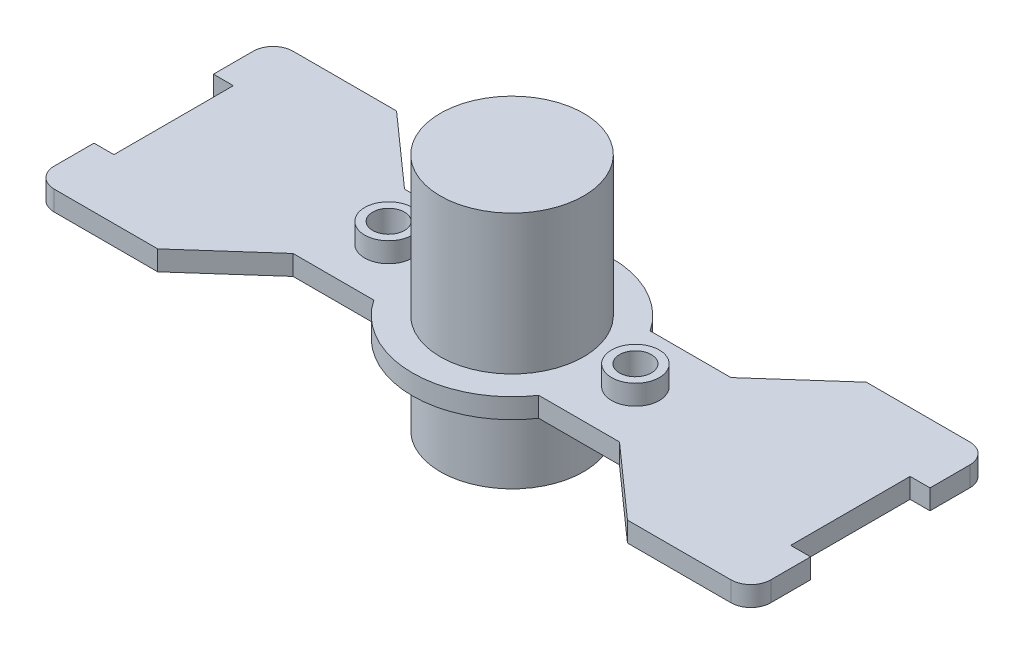
SolidWorks part; units mm, degrees
ref_plane "前视基准面" through (0, 0, 0) normal (0, 0, 1) x (1, 0, 0)
ref_plane "上视基准面" through (0, 0, 0) normal (0, 1, 0) x (1, 0, 0)
ref_plane "右视基准面" through (0, 0, 0) normal (1, 0, 0) x (0, 0, -1)
sketch "草图1" plane through (0, 0, 0) normal (0, 1, 0) x (1, 0, 0)
  line L0 (0, 0) -> (0, 25) construction
  line L1 (-20.7123, 14) -> (-41, 14)
  line L2 (-41, 14) -> (-59, 30)
  line L3 (-59, 30) -> (-90, 30)
  line L4 (-90, 30) -> (-90, 15)
  line L5 (-90, 15) -> (-85, 15)
  line L6 (-85, 15) -> (-85, -15)
  line L7 (-85, -15) -> (-90, -15)
  line L8 (-90, -15) -> (-90, -30)
  line L9 (-90, -30) -> (-59, -30)
  line L10 (-59, -30) -> (-41, -14)
  line L11 (-41, -14) -> (-20.7123, -14)
  line L12 (0, 0) -> (-85, 0) construction
  line L13 (90, -30) -> (59, -30)
  line L14 (59, 30) -> (90, 30)
  line L15 (41, -14) -> (20.7123, -14)
  line L16 (59, -30) -> (41, -14)
  line L17 (90, -15) -> (90, -30)
  line L18 (85, -15) -> (90, -15)
  line L19 (85, 15) -> (85, -15)
  line L20 (90, 15) -> (85, 15)
  line L21 (90, 30) -> (90, 15)
  line L22 (41, 14) -> (59, 30)
  line L23 (20.7123, 14) -> (41, 14)
  arc A0 (-20.7123, -14) -> (20.7123, -14) centre (0, 0) ccw
  arc A1 (20.7123, 14) -> (-20.7123, 14) centre (0, 0) ccw
  point P17 (0, 0)
  point P18 (0, 0)
  point P19 (0, 0)
  dimension "D1" = 50
  dimension "D2" = 41
  dimension "D3" = 118
  dimension "D4" = 180
  dimension "D5" = 170
  dimension "D6" = 30
  dimension "D7" = 60
  dimension "D8" = 28
extrude "凸台-拉伸1" add sketch "草图1" along normal blind 5
sketch "草图2" plane through (0, 5, 0) normal (0, 1, 0) x (1, 0, 0)
  circle A0 centre (0, 0) radius 18
  dimension "D1" = 36
extrude "凸台-拉伸2" add sketch "草图2" along normal blind 35 and the other way blind 25
sketch "草图3" plane through (0, -20, 0) normal (0, -1, 0) x (1, 0, 0)
  circle A0 centre (0, 0) radius 15
  dimension "D1" = 30
extrude "切除-拉伸1" cut sketch "草图3" against normal blind 55
sketch "草图4" plane through (0, 5, 0) normal (0, 1, 0) x (1, 0, 0)
  circle A0 centre (-31, 0) radius 6
  circle A1 centre (31, 0) radius 6
  circle A2 centre (31, 0) radius 4
  circle A3 centre (-31, 0) radius 4
  point P6 (0, 0)
  dimension "D1" = 8
  dimension "D2" = 12
  dimension "D3" = 12
  dimension "D4" = 8
  dimension "D5" = 62
  dimension "D6" = 31
extrude "凸台-拉伸3" add sketch "草图4" along normal blind 5
sketch "草图5" plane through (0, 5, 0) normal (0, 1, 0) x (1, 0, 0)
  circle A0 centre (31, 0) radius 4 construction
  circle A1 centre (-31, 0) radius 4 construction
  circle A2 centre (31, 0) radius 4
  circle A3 centre (-31, 0) radius 4
extrude "切除-拉伸2" cut sketch "草图5" against normal through all
fillet "圆角1" radius 5 4 edges at (90, 2.5, -30) (90, 2.5, 30) (-90, 2.5, 30) (-90, 2.5, -30)
